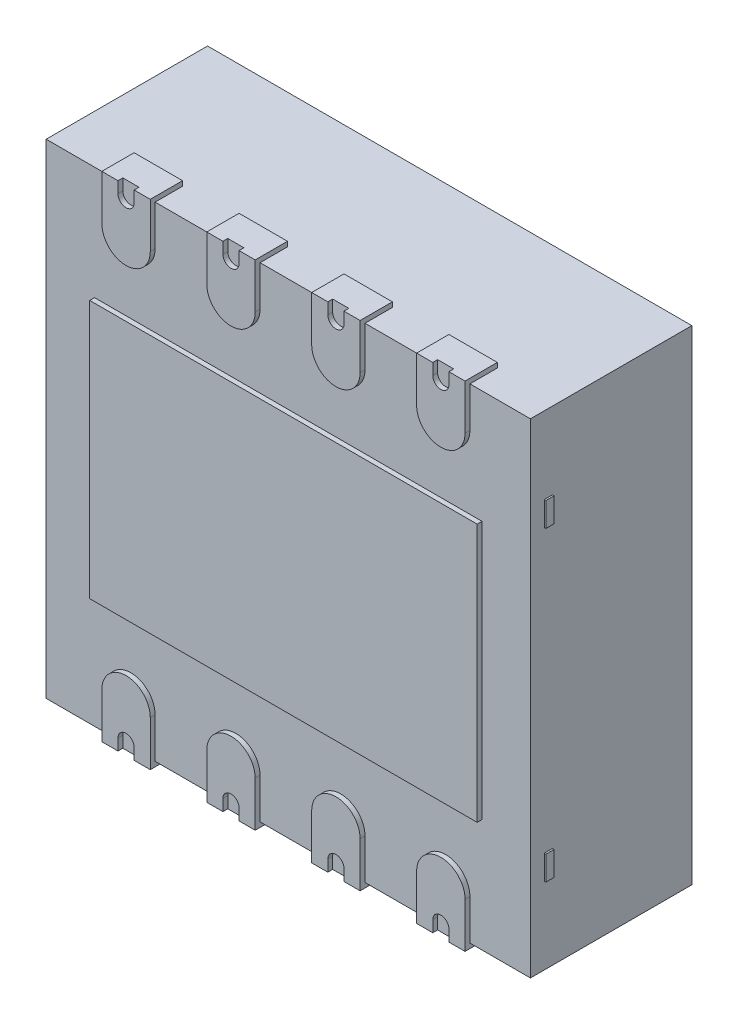
SolidWorks part; units mm, degrees
ref_plane "Front Plane" through (0, 0, 0) normal (0, 0, 1) x (1, 0, 0)
ref_plane "Top Plane" through (0, 0, 0) normal (0, 1, 0) x (1, 0, 0)
ref_plane "Right Plane" through (0, 0, 0) normal (1, 0, 0) x (0, 0, -1)
sketch "Sketch1" plane through (0, 0, 0) normal (0, 0, 1) x (1, 0, 0)
  line L1 (1.5, 1.5) -> (-1.5, 1.5)
  line L2 (1.5, 1.5) -> (1.5, -1.5)
  line L3 (1.5, -1.5) -> (-1.5, -1.5)
  line L4 (-1.5, 1.5) -> (-1.5, -1.5)
  line L5 (1.5, 1.5) -> (-1.5, -1.5) construction
  line L6 (1.5, -1.5) -> (-1.5, 1.5) construction
  point P0 (0, 0)
  dimension "D1" = 3
  dimension "D2" = 3
extrude "Boss-Extrude1" add sketch "Sketch1" against normal blind 1
sketch "Sketch2" plane through (0, 0, 0) normal (0, 0, 1) x (-1, 0, 0)
  line L0 (-0.975, 1.25) -> (-0.975, 1.6035) construction
  line L1 (1.2, 0.8) -> (-1.2, 0.8)
  line L2 (1.2, 0.8) -> (1.2, -0.8)
  line L3 (1.2, -0.8) -> (-1.2, -0.8)
  line L4 (-1.2, 0.8) -> (-1.2, -0.8)
  line L5 (1.2, 0.8) -> (-1.2, -0.8) construction
  line L6 (1.2, -0.8) -> (-1.2, 0.8) construction
  line L7 (-1.125, 1.25) -> (-1.125, 1.6035)
  line L8 (-0.825, 1.25) -> (-0.825, 1.6035)
  line L9 (1.5, 1.5) -> (-1.5, 1.5) construction
  line L10 (-0.175, 1.25) -> (-0.175, 1.6035)
  line L11 (-0.475, 1.25) -> (-0.475, 1.6035)
  line L12 (-0.325, 1.25) -> (-0.325, 1.6035) construction
  line L13 (0.475, 1.25) -> (0.475, 1.6035)
  line L14 (0.175, 1.25) -> (0.175, 1.6035)
  line L15 (0.325, 1.25) -> (0.325, 1.6035) construction
  line L16 (1.125, 1.25) -> (1.125, 1.6035)
  line L17 (0.825, 1.25) -> (0.825, 1.6035)
  line L18 (0.975, 1.25) -> (0.975, 1.6035) construction
  line L19 (0, 0) -> (0.825, 0) construction
  line L20 (-0.975, -1.25) -> (-0.975, -1.6035) construction
  line L21 (-1.125, -1.25) -> (-1.125, -1.6035)
  line L22 (-0.825, -1.25) -> (-0.825, -1.6035)
  line L23 (-0.325, -1.25) -> (-0.325, -1.6035) construction
  line L24 (-0.475, -1.25) -> (-0.475, -1.6035)
  line L25 (-0.175, -1.25) -> (-0.175, -1.6035)
  line L26 (0.325, -1.25) -> (0.325, -1.6035) construction
  line L27 (0.175, -1.25) -> (0.175, -1.6035)
  line L28 (0.475, -1.25) -> (0.475, -1.6035)
  line L29 (0.975, -1.25) -> (0.975, -1.6035) construction
  line L30 (0.825, -1.25) -> (0.825, -1.6035)
  line L31 (1.125, -1.25) -> (1.125, -1.6035)
  arc A0 (-1.125, 1.25) -> (-0.825, 1.25) centre (-0.975, 1.25) ccw
  arc A1 (-0.825, 1.6035) -> (-1.125, 1.6035) centre (-0.975, 1.6035) ccw
  arc A2 (-0.475, 1.25) -> (-0.175, 1.25) centre (-0.325, 1.25) ccw
  arc A3 (-0.175, 1.6035) -> (-0.475, 1.6035) centre (-0.325, 1.6035) ccw
  arc A4 (0.175, 1.25) -> (0.475, 1.25) centre (0.325, 1.25) ccw
  arc A5 (0.475, 1.6035) -> (0.175, 1.6035) centre (0.325, 1.6035) ccw
  arc A6 (0.825, 1.25) -> (1.125, 1.25) centre (0.975, 1.25) ccw
  arc A7 (1.125, 1.6035) -> (0.825, 1.6035) centre (0.975, 1.6035) ccw
  arc A8 (-1.125, -1.25) -> (-0.825, -1.25) centre (-0.975, -1.25) cw
  arc A9 (-0.825, -1.6035) -> (-1.125, -1.6035) centre (-0.975, -1.6035) cw
  arc A10 (-0.475, -1.25) -> (-0.175, -1.25) centre (-0.325, -1.25) cw
  arc A11 (-0.175, -1.6035) -> (-0.475, -1.6035) centre (-0.325, -1.6035) cw
  arc A12 (0.175, -1.25) -> (0.475, -1.25) centre (0.325, -1.25) cw
  arc A13 (0.475, -1.6035) -> (0.175, -1.6035) centre (0.325, -1.6035) cw
  arc A14 (0.825, -1.25) -> (1.125, -1.25) centre (0.975, -1.25) cw
  arc A15 (1.125, -1.6035) -> (0.825, -1.6035) centre (0.975, -1.6035) cw
  point P0 (0, 0)
  point P8 (-0.975, 1.4268)
  point P13 (-0.975, 1.1)
  point P19 (-0.325, 1.4268)
  point P26 (0.325, 1.4268)
  point P33 (0.975, 1.4268)
  point P41 (-0.975, -1.4268)
  point P48 (-0.325, -1.4268)
  point P55 (0.325, -1.4268)
  point P62 (0.975, -1.4268)
  dimension "D1" = 1.6
  dimension "D2" = 2.4
  dimension "D3" = 0.3
  dimension "D4" = 0.4
  dimension "D5" = 0.975
  dimension "D6" = 4
extrude "Boss-Extrude2" add sketch "Sketch2" along normal blind 0.03
sketch "Sketch4" plane through (0, 0, -1) normal (0, 0, -1) x (-1, 0, 0)
  line L1 (1.5, 1.5) -> (-1.5, 1.5)
  line L2 (1.5, 1.5) -> (1.5, -1.5)
  line L3 (1.5, -1.5) -> (-1.5, -1.5)
  line L4 (-1.5, 1.5) -> (-1.5, -1.5)
  line L5 (-2.0468, 1.8988) -> (1.8937, 1.8988)
  line L6 (-2.0468, 1.8988) -> (-2.0468, -1.9448)
  line L7 (-2.0468, -1.9448) -> (1.8937, -1.9448)
  line L8 (1.8937, 1.8988) -> (1.8937, -1.9448)
extrude "Cut-Extrude1" cut sketch "Sketch4" against normal blind 60.05
sketch "Sketch7" plane through (0, -1.5, 0) normal (0, -1, 0) x (1, 0, 0)
  line L0 (0.825, 0.03) -> (0.825, 0) construction
  line L1 (1.125, -0.17) -> (0.825, -0.17)
  line L2 (1.125, -0.17) -> (1.125, 0.03)
  line L3 (1.125, 0.03) -> (0.825, 0.03)
  line L4 (0.825, -0.17) -> (0.825, 0.03)
  line L5 (0.175, 0.03) -> (0.175, 0) construction
  line L6 (0.475, -0.17) -> (0.175, -0.17)
  line L7 (0.475, -0.17) -> (0.475, 0.03)
  line L8 (0.475, 0.03) -> (0.175, 0.03)
  line L9 (0.175, -0.17) -> (0.175, 0.03)
  line L10 (-0.475, 0.03) -> (-0.475, 0) construction
  line L11 (-0.175, -0.17) -> (-0.475, -0.17)
  line L12 (-0.175, -0.17) -> (-0.175, 0.03)
  line L13 (-0.175, 0.03) -> (-0.475, 0.03)
  line L14 (-0.475, -0.17) -> (-0.475, 0.03)
  line L15 (-1.125, 0.03) -> (-1.125, 0) construction
  line L16 (-0.825, -0.17) -> (-1.125, -0.17)
  line L17 (-0.825, -0.17) -> (-0.825, 0.03)
  line L18 (-0.825, 0.03) -> (-1.125, 0.03)
  line L19 (-1.125, -0.17) -> (-1.125, 0.03)
  point P7 (0.825, 0.015)
  point P22 (-0.475, 0.015)
  dimension "D1" = 0
  dimension "D2" = 0
  dimension "D3" = 0
  dimension "D4" = 0
  dimension "D5" = 0.2
  dimension "D6" = 0.2
  dimension "D7" = 0.2
  dimension "D8" = 0.2
extrude "Boss-Extrude3" add sketch "Sketch7" along normal blind 0.03
mirror "Mirror1" about plane through (0, 0, 0) normal (0, 1, 0) of "Boss-Extrude3"
sketch "Sketch8" plane through (0, 0, 0.03) normal (0, 0, 1) x (-1, 0, 0)
  line L0 (-0.975, 1.6098) -> (-0.975, 1.4598) construction
  line L1 (-0.925, 1.6098) -> (-0.925, 1.4598)
  line L2 (-1.025, 1.6098) -> (-1.025, 1.4598)
  line L3 (-0.375, 1.6098) -> (-0.375, 1.4598)
  line L6 (-0.275, 1.6098) -> (-0.275, 1.4598)
  line L9 (-0.325, 1.6098) -> (-0.325, 1.4598) construction
  line L13 (0.275, 1.6098) -> (0.275, 1.4598)
  line L15 (0.375, 1.6098) -> (0.375, 1.4598)
  line L16 (0.325, 1.6098) -> (0.325, 1.4598) construction
  line L17 (0.925, 1.6098) -> (0.925, 1.4598)
  line L18 (1.025, 1.6098) -> (1.025, 1.4598)
  line L19 (0.975, 1.6098) -> (0.975, 1.4598) construction
  line L20 (0, 0) -> (0.4114, 0) construction
  line L21 (-0.975, -1.6098) -> (-0.975, -1.4598) construction
  line L22 (-0.925, -1.6098) -> (-0.925, -1.4598)
  line L23 (-1.025, -1.6098) -> (-1.025, -1.4598)
  line L24 (-0.325, -1.6098) -> (-0.325, -1.4598) construction
  line L25 (-0.275, -1.6098) -> (-0.275, -1.4598)
  line L26 (-0.375, -1.6098) -> (-0.375, -1.4598)
  line L27 (0.325, -1.6098) -> (0.325, -1.4598) construction
  line L28 (0.375, -1.6098) -> (0.375, -1.4598)
  line L29 (0.275, -1.6098) -> (0.275, -1.4598)
  line L30 (0.975, -1.6098) -> (0.975, -1.4598) construction
  line L31 (1.025, -1.6098) -> (1.025, -1.4598)
  line L32 (0.925, -1.6098) -> (0.925, -1.4598)
  arc A0 (-0.925, 1.6098) -> (-1.025, 1.6098) centre (-0.975, 1.6098) ccw
  arc A1 (-1.025, 1.4598) -> (-0.925, 1.4598) centre (-0.975, 1.4598) ccw
  arc A8 (-0.275, 1.6098) -> (-0.375, 1.6098) centre (-0.325, 1.6098) ccw
  arc A9 (-0.375, 1.4598) -> (-0.275, 1.4598) centre (-0.325, 1.4598) ccw
  arc A10 (0.375, 1.6098) -> (0.275, 1.6098) centre (0.325, 1.6098) ccw
  arc A11 (0.275, 1.4598) -> (0.375, 1.4598) centre (0.325, 1.4598) ccw
  arc A12 (1.025, 1.6098) -> (0.925, 1.6098) centre (0.975, 1.6098) ccw
  arc A13 (0.925, 1.4598) -> (1.025, 1.4598) centre (0.975, 1.4598) ccw
  arc A14 (-0.925, -1.6098) -> (-1.025, -1.6098) centre (-0.975, -1.6098) cw
  arc A15 (-1.025, -1.4598) -> (-0.925, -1.4598) centre (-0.975, -1.4598) cw
  arc A16 (-0.275, -1.6098) -> (-0.375, -1.6098) centre (-0.325, -1.6098) cw
  arc A17 (-0.375, -1.4598) -> (-0.275, -1.4598) centre (-0.325, -1.4598) cw
  arc A18 (0.375, -1.6098) -> (0.275, -1.6098) centre (0.325, -1.6098) cw
  arc A19 (0.275, -1.4598) -> (0.375, -1.4598) centre (0.325, -1.4598) cw
  arc A20 (1.025, -1.6098) -> (0.925, -1.6098) centre (0.975, -1.6098) cw
  arc A21 (0.925, -1.4598) -> (1.025, -1.4598) centre (0.975, -1.4598) cw
  point P2 (-0.975, 1.5348)
  point P11 (-0.325, 1.5348)
  point P18 (0.325, 1.5348)
  point P25 (0.975, 1.5348)
  point P32 (-0.975, -1.5348)
  point P40 (-0.325, -1.5348)
  point P47 (0.325, -1.5348)
  point P54 (0.975, -1.5348)
  dimension "D1" = 0.05
  dimension "D2" = 4
  dimension "D3" = 0.15
extrude "Cut-Extrude2" cut sketch "Sketch8" against normal blind 0.03
sketch "Sketch9" plane through (-1.5, 0, 0) normal (-1, 0, 0) x (0, 0, 1)
  line L0 (0, 0) -> (-0.4231, 0) construction
  line L1 (-0.0858, 1.0236) -> (-0.0858, 0.8736)
  line L2 (-0.0858, 1.0236) -> (-0.1358, 1.0236)
  line L3 (-0.1358, 1.0236) -> (-0.1358, 0.8736)
  line L4 (-0.0858, 0.8736) -> (-0.1358, 0.8736)
  line L5 (-0.0858, -0.8736) -> (-0.1358, -0.8736)
  line L6 (-0.1358, -1.0236) -> (-0.1358, -0.8736)
  line L7 (-0.0858, -1.0236) -> (-0.1358, -1.0236)
  line L8 (-0.0858, -1.0236) -> (-0.0858, -0.8736)
  dimension "D1" = 0.15
  dimension "D2" = 0.05
extrude "Boss-Extrude4" add sketch "Sketch9" along normal blind 0.01
mirror "Mirror2" about plane through (0, 0, 0) normal (1, 0, 0) of "Boss-Extrude4"
sketch "Sketch11" plane through (0, 0, -1) normal (0, 0, -1) x (-1, 0, 0)
  line L0 (70.7212, 256.2979) -> (518.7212, 256.2979) construction
  line L54 (-0.8059, 1.0381) -> (-0.4233, 0.6054)
  line L55 (-0.3623, 0.9997) -> (-0.1188, 0.9997)
  line L56 (0.473, 0.2478) -> (0.2316, 0.2478)
  line L57 (-0.4233, 1.0381) -> (-0.0972, 1.0381)
  line L58 (-0.7882, 0.654) -> (-0.7882, 0.2148)
  line L59 (-0.1188, 0.9997) -> (0.0552, 0.7211)
  line L60 (-0.0933, 0.2106) -> (-0.3961, 0.2106)
  line L61 (-0.7882, 0.2148) -> (-1.0676, 0.2148)
  line L62 (0.5173, 0.9997) -> (0.9108, 0.9942)
  line L63 (0.5012, 0.8902) -> (0.5012, 0.6704)
  line L64 (0.9437, 0.5264) -> (0.5435, 0.5264)
  line L65 (-1.0282, 0.2545) -> (-1.0282, 0.9912)
  line L66 (0.5397, 0.8504) -> (0.8294, 0.8504)
  line L67 (1.0527, 0.8482) -> (1.0507, 0.7013)
  line L68 (0.8774, 0.8024) -> (0.8774, 0.7608)
  line L69 (-1.0676, 0.2148) -> (-1.0676, 1.0381)
  line L70 (0.5435, 0.2064) -> (0.2018, 0.2064)
  line L71 (-0.1256, 0.6262) -> (-0.3623, 0.9997)
  line L72 (0.5012, 0.5594) -> (0.5012, 0.27)
  line L73 (0.2018, 1.0381) -> (0.9437, 1.0381)
  line L74 (-0.3744, 0.4818) -> (-0.3744, 0.9397)
  line L75 (0.2391, 0.6223) -> (0.473, 0.2478)
  line L76 (0.2018, 0.2064) -> (0.0526, 0.4469)
  line L77 (-0.3981, 0.2613) -> (-0.8255, 0.7578)
  line L78 (0.2887, 0.6223) -> (0.5173, 0.9997)
  line L79 (0.8742, 0.6704) -> (0.5012, 0.6704)
  line L80 (1.0877, 0.8941) -> (1.0877, 0.6704)
  line L81 (-0.3961, 0.2106) -> (-0.7882, 0.654)
  line L82 (0.0552, 0.5301) -> (-0.1126, 0.2502)
  line L83 (0.0526, 0.7966) -> (0.2018, 1.0381)
  line L84 (0.0552, 0.7211) -> (0.2223, 0.9997)
  line L85 (-0.3623, 0.2502) -> (-0.1256, 0.6262)
  line L86 (-0.3744, 0.9397) -> (-0.1788, 0.6262)
  line L87 (0.2223, 0.9997) -> (0.4653, 0.9997)
  line L88 (0.5397, 0.8504) -> (0.5397, 0.7128)
  line L89 (-0.1126, 0.2502) -> (-0.3623, 0.2502)
  line L90 (0.5397, 0.7128) -> (0.8294, 0.7128)
  line L91 (0.2316, 0.2478) -> (0.0552, 0.5301)
  line L92 (0.5012, 0.8902) -> (0.8742, 0.8902)
  line L93 (0.5435, 0.5264) -> (0.5435, 0.2064)
  line L94 (-0.8129, 0.9912) -> (-0.3744, 0.4818)
  line L95 (0.9222, 0.8422) -> (0.9222, 0.7184)
  line L96 (-0.0972, 1.0381) -> (0.0526, 0.7966)
  line L97 (0.0526, 0.4469) -> (-0.0933, 0.2106)
  line L98 (-0.8255, 0.2545) -> (-1.0282, 0.2545)
  line L99 (0.9067, 0.5594) -> (0.5012, 0.5594)
  line L100 (-1.0676, 1.0381) -> (-0.8059, 1.0381)
  line L101 (-0.1788, 0.6262) -> (-0.3981, 0.2613)
  line L102 (0.4653, 0.9997) -> (0.2391, 0.6223)
  line L103 (-0.4233, 0.6054) -> (-0.4233, 1.0381)
  line L104 (-1.0282, 0.9912) -> (-0.8129, 0.9912)
  line L105 (-0.8255, 0.7578) -> (-0.8255, 0.2545)
  line L106 (0.5012, 0.27) -> (0.2887, 0.6223)
  arc A8 (0.8742, 0.8902) -> (0.9222, 0.8422) centre (0.8742, 0.8422) cw
  arc A9 (0.9437, 1.0381) -> (1.0877, 0.8941) centre (0.9437, 0.8941) cw
  arc A10 (0.9222, 0.7184) -> (0.8742, 0.6704) centre (0.8742, 0.7184) cw
  arc A11 (1.0877, 0.6704) -> (0.9437, 0.5264) centre (0.9437, 0.6704) cw
  arc A12 (0.8294, 0.8504) -> (0.8774, 0.8024) centre (0.8294, 0.8024) cw
  arc A13 (1.0507, 0.7013) -> (0.9067, 0.5594) centre (0.9067, 0.7034) cw
  arc A14 (0.8294, 0.7128) -> (0.8774, 0.7608) centre (0.8294, 0.7608) ccw
  arc A15 (0.9108, 0.9942) -> (1.0527, 0.8482) centre (0.9087, 0.8502) cw
sketch "Sketch12" plane through (0, 0, -1) normal (0, 0, -1) x (-1, 0, 0)
  line L0 (-1.0422, -0.9486) -> (0.9798, -0.9486) construction
  text T0 "<b>TJA1442</b>" font "Century Gothic" height 0.4
extrude "Boss-Extrude9" add sketch "Sketch11" along normal blind 0.01 contours A11 L80 A9 L73 L83 L96 L57 L103 L54 L100 L69 L61 L58 L81 L60 L97 L76 L70 L93 L64 L87 L102 L75 L56 L91 L82 L89 L85 L71 L55 L59 L84 L77 L105 L98 L65 L104 L94 L74 L86 L101 L62 A15 L67 A13 L99 L72 L106 | A10 L95 A8 L92 L63 L79 A14 L90 L88 L66 A12 L68
extrude "Boss-Extrude10" add sketch "Sketch12" along normal blind 0.01
